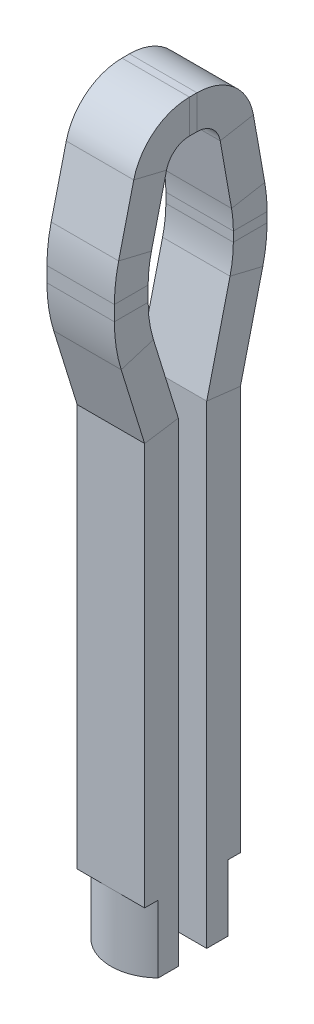
SolidWorks part; units mm, degrees
ref_plane "Alzado" through (0, 0, 0) normal (0, 0, 1) x (1, 0, 0)
ref_plane "Planta" through (0, 0, 0) normal (0, 1, 0) x (1, 0, 0)
ref_plane "Vista lateral" through (0, 0, 0) normal (1, 0, 0) x (0, 0, -1)
sketch "Croquis1" plane through (0, 0, 0) normal (0, 1, 0) x (1, 0, 0)
  line L1 (0, 0) -> (5, 0)
  line L2 (0, 0) -> (0, -2.5)
  line L3 (0, -2.5) -> (5, -2.5)
  line L4 (5, 0) -> (5, -2.5)
  dimension "D1" = 5
  dimension "D2" = 2.5
extrude "Saliente-Extruir1" add sketch "Croquis1" along normal blind 5
sketch3d "Croquis3D1"
  line L0 (2.5, 5, 0) -> (2.5, 5, 2.5) construction
  line L1 (5, 5, 0) -> (0, 5, 0) construction
  line L2 (0, 5, 2.5) -> (5, 5, 2.5) construction
  line L3 (2.5, 5, 1.25) -> (2.5, 35, 1.25)
  line L4 (2.5, 35, 1.25) -> (2.5, 40.7867, 3.0424)
  line L5 (2.5, 43.7455, 3.4902) -> (2.5, 44.8541, 3.4902)
  line L6 (2.5, 47.2008, 3.2109) -> (2.5, 51.8402, 2.0909)
  line L7 (2.5, 54.1362, -0.8253) -> (2.5, 54.1362, -1.3783)
  line L8 (2.5, 51.6575, -4.3326) -> (2.5, 46.8984, -5.1725)
  line L9 (2.5, 45.1605, -5.3246) -> (2.5, 44.4393, -5.3246)
  line L10 (2.5, 42.0926, -5.0454) -> (2.5, 35.0838, -3.3534)
  line L11 (2.5, 35.0838, -3.3534) -> (2.5, 0.1009, -3.3534)
  arc A0 (2.5, 44.4393, -5.3246) -> (2.5, 42.0926, -5.0454) centre (2.5, 44.4393, 4.6754) ccw
  arc A1 (2.5, 46.8984, -5.1725) -> (2.5, 45.1605, -5.3246) centre (2.5, 45.1605, 4.6754) ccw
  arc A2 (2.5, 44.8541, 3.4902) -> (2.5, 47.2008, 3.2109) centre (2.5, 44.8541, -6.5098) ccw
  arc A3 (2.5, 40.7867, 3.0424) -> (2.5, 43.7455, 3.4902) centre (2.5, 43.7455, -6.5098) ccw
  arc A4 (2.5, 54.1362, -1.3783) -> (2.5, 51.6575, -4.3326) centre (2.5, 51.1362, -1.3783) ccw
  arc A5 (2.5, 51.8402, 2.0909) -> (2.5, 54.1362, -0.8253) centre (2.5, 51.1362, -0.8253) ccw
  point P18 (2.5, 43.2494, -5.3246)
  point P19 (-7.5, 44.4393, 4.6754)
  point P22 (2.5, 46.0361, -5.3246)
  point P23 (-7.5, 45.1605, 4.6754)
  point P26 (2.5, 46.044, 3.4902)
  point P27 (-7.5, 44.8541, -6.5098)
  point P30 (2.5, 42.2322, 3.4902)
  point P31 (-7.5, 43.7455, -6.5098)
  point P34 (2.5, 54.1362, -3.8952)
  point P35 (-0.5, 51.1362, -1.3783)
  point P38 (2.5, 54.1362, 1.5366)
  point P39 (-0.5, 51.1362, -0.8253)
  dimension "D2" = 10
  dimension "D3" = 3
  dimension "D1" = 30
sketch "Croquis2" plane through (0, 5, 0) normal (0, 1, 0) x (1, 0, 0)
  line L1 (0, -2.5) -> (5, -2.5)
  line L2 (0, -2.5) -> (0, 0)
  line L3 (0, 0) -> (5, 0)
  line L4 (5, -2.5) -> (5, 0)
sweep "Barrer1" add profiles "Croquis2" path "Croquis3D1"
sketch "Croquis3" plane through (0, 0, 0) normal (0, -1, 0) x (1, 0, 0)
  line L0 (2.5, -0.8253) -> (2.5, -1.3783) construction
  line L1 (5, -0.8253) -> (0, -0.8253) construction
  line L2 (5, -1.3783) -> (0, -1.3783) construction
  circle A0 centre (2.5, -1.1018) radius 3.6018
  circle A1 centre (2.5, -1.1018) radius 5.9208
extrude "Cortar-Extruir1" cut sketch "Croquis3" against normal blind 5
